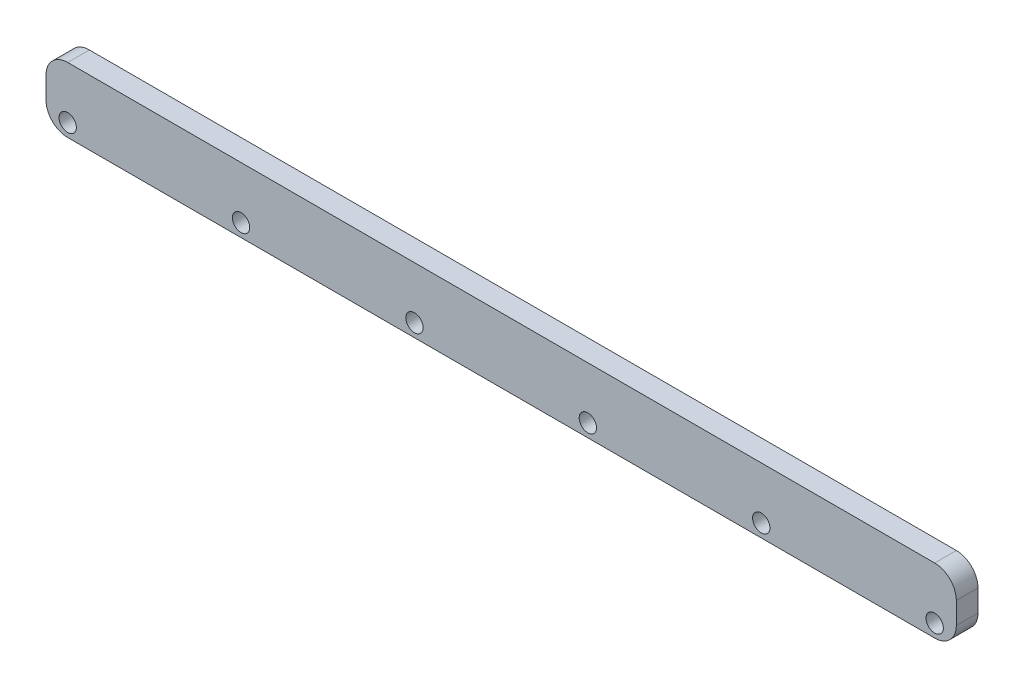
SolidWorks part; units mm, degrees
ref_plane "Plan de face" through (0, 0, 0) normal (0, 0, 1) x (1, 0, 0)
ref_plane "Plan de dessus" through (0, 0, 0) normal (0, 1, 0) x (1, 0, 0)
ref_plane "Plan de droite" through (0, 0, 0) normal (1, 0, 0) x (0, 0, -1)
sketch "Esquisse1" plane through (0, 0, 0) normal (0, 0, 1) x (1, 0, 0)
  line L0 (0, 3) -> (210, 3) construction
  line L1 (0, 0) -> (210, 0)
  line L2 (0, 0) -> (0, 15)
  line L3 (0, 15) -> (210, 15)
  line L4 (210, 0) -> (210, 15)
  circle A0 centre (5, 3) radius 2
  circle A1 centre (45, 3) radius 2
  circle A2 centre (85, 3) radius 2
  circle A3 centre (125, 3) radius 2
  circle A4 centre (165, 3) radius 2
  circle A5 centre (205, 3) radius 2
  point P9 (176.2462, 0)
  point P20 (216.3366, 0)
  dimension "D1" = 4
  dimension "D2" = 3
  dimension "D3" = 12
  dimension "D4" = 5
  dimension "D5" = 5
  dimension "D6" = 40
  dimension "D7" = 6
extrude "Boss.-Extru.1" add sketch "Esquisse1" along normal blind 5
fillet "Congé1" radius 5 4 edges at (210, 0, 2.5) (210, 15, 2.5) (0, 0, 2.5) (0, 15, 2.5)
